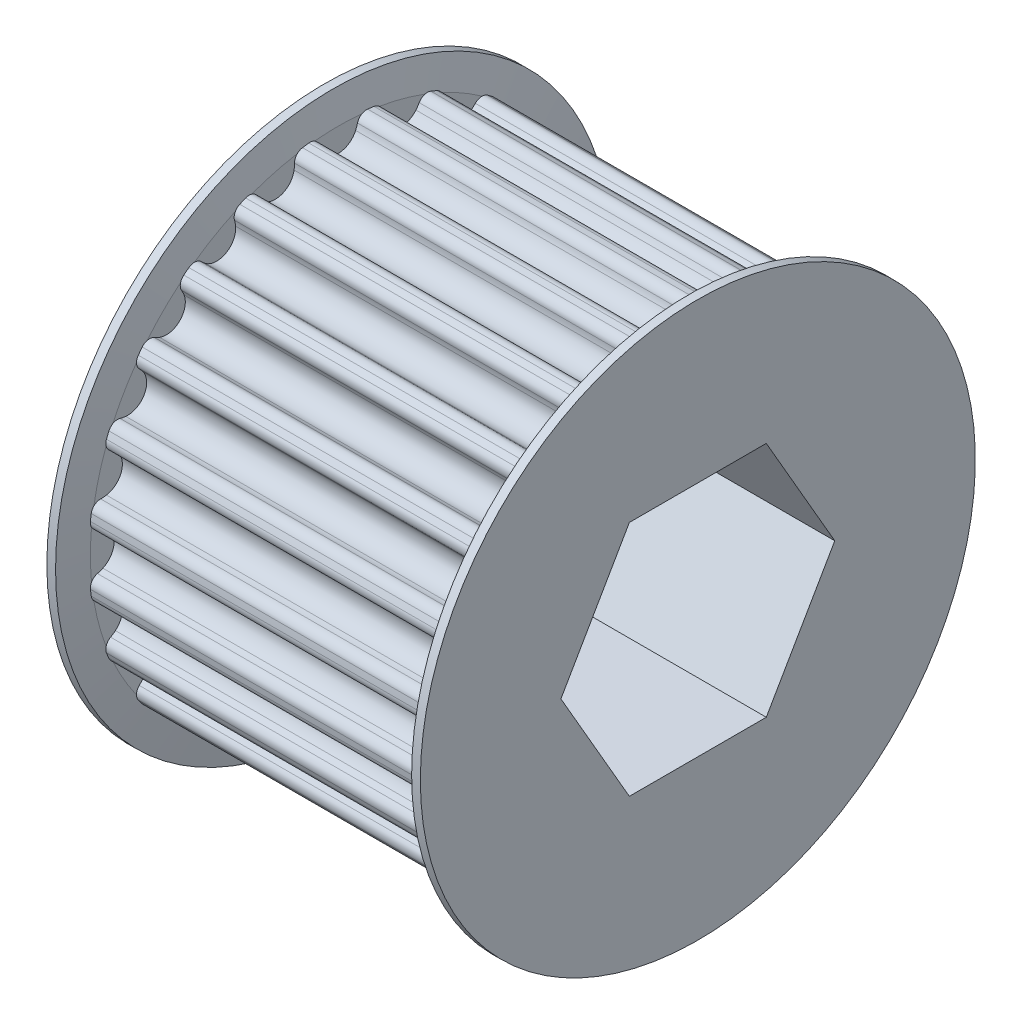
SolidWorks part; units mm, degrees
material "PET"
ref_plane "Front" through (0, 0, 0) normal (0, 0, 1) x (1, 0, 0)
ref_plane "Top" through (0, 0, 0) normal (0, 1, 0) x (1, 0, 0)
ref_plane "Right" through (0, 0, 0) normal (1, 0, 0) x (0, 0, -1)
sketch "Sketch1" plane through (0, 0, 0) normal (1, 0, 0) x (0, 0, -1)
  arc A0 (5.5576, 11.6856) -> (5.2736, 12.2806) centre (5.0763, 11.8212) ccw
  arc A1 (5.2736, 12.2806) -> (4.9547, 12.4127) centre (0, 0) ccw
  arc A2 (4.9547, 12.4127) -> (4.3332, 12.1928) centre (4.7694, 11.9483) ccw
  arc A3 (4.1589, 11.936) -> (4.3332, 12.1928) centre (2.7488, 13.0808) ccw
  arc A4 (2.3663, 12.4163) -> (4.1589, 11.936) centre (3.3699, 12.5766) ccw
  arc A5 (2.3437, 12.7258) -> (2.3663, 12.4163) centre (4.1598, 12.7027) ccw
  arc A6 (2.3437, 12.7258) -> (1.9154, 13.2271) centre (1.8438, 12.7322) ccw
  arc A7 (1.9154, 13.2271) -> (1.5733, 13.2721) centre (0, 0) ccw
  arc A8 (1.5733, 13.2721) -> (1.0298, 12.8988) centre (1.5144, 12.7756) ccw
  arc A9 (0.9279, 12.6057) -> (1.0298, 12.8988) centre (-0.7304, 13.3465) ccw
  arc A10 (-0.9279, 12.6057) -> (0.9279, 12.6057) centre (0, 13.0202) ccw
  arc A11 (-1.0298, 12.8988) -> (-0.9279, 12.6057) centre (0.7304, 13.3465) ccw
  arc A12 (-1.0298, 12.8988) -> (-1.5733, 13.2721) centre (-1.5144, 12.7756) ccw
  arc A13 (-1.5733, 13.2721) -> (-1.9154, 13.2271) centre (0, 0) ccw
  arc A14 (-1.9154, 13.2271) -> (-2.3437, 12.7258) centre (-1.8438, 12.7322) ccw
  arc A15 (-2.3663, 12.4163) -> (-2.3437, 12.7258) centre (-4.1598, 12.7027) ccw
  arc A16 (-4.1589, 11.936) -> (-2.3663, 12.4163) centre (-3.3699, 12.5766) ccw
  arc A17 (-4.3332, 12.1928) -> (-4.1589, 11.936) centre (-2.7488, 13.0808) ccw
  arc A18 (-4.3332, 12.1928) -> (-4.9547, 12.4127) centre (-4.7694, 11.9483) ccw
  arc A19 (-4.9547, 12.4127) -> (-5.2736, 12.2806) centre (0, 0) ccw
  arc A20 (-5.2736, 12.2806) -> (-5.5576, 11.6856) centre (-5.0763, 11.8212) ccw
  arc A21 (-5.4993, 11.3808) -> (-5.5576, 11.6856) centre (-7.3058, 11.1932) ccw
  arc A22 (-7.1064, 10.4529) -> (-5.4993, 11.3808) centre (-6.5101, 11.2758) ccw
  arc A23 (-7.3413, 10.6558) -> (-7.1064, 10.4529) centre (-6.0407, 11.9236) ccw
  arc A24 (-7.3413, 10.6558) -> (-7.9986, 10.7074) centre (-7.6993, 10.3068) ccw
  arc A25 (-7.9986, 10.7074) -> (-8.2723, 10.4973) centre (0, 0) ccw
  arc A26 (-8.2723, 10.4973) -> (-8.3927, 9.849) centre (-7.9628, 10.1045) ccw
  arc A27 (-8.2575, 9.5697) -> (-8.3927, 9.849) centre (-9.9539, 8.9209) ccw
  arc A28 (-9.5697, 8.2575) -> (-8.2575, 9.5697) centre (-9.2067, 9.2067) ccw
  arc A29 (-9.849, 8.3927) -> (-9.5697, 8.2575) centre (-8.9209, 9.9539) ccw
  arc A30 (-9.849, 8.3927) -> (-10.4973, 8.2723) centre (-10.1045, 7.9628) ccw
  arc A31 (-10.4973, 8.2723) -> (-10.7074, 7.9986) centre (0, 0) ccw
  arc A32 (-10.7074, 7.9986) -> (-10.6558, 7.3413) centre (-10.3068, 7.6993) ccw
  arc A33 (-10.4529, 7.1064) -> (-10.6558, 7.3413) centre (-11.9236, 6.0407) ccw
  arc A34 (-11.3808, 5.4993) -> (-10.4529, 7.1064) centre (-11.2758, 6.5101) ccw
  arc A35 (-11.6856, 5.5576) -> (-11.3808, 5.4993) centre (-11.1932, 7.3058) ccw
  arc A36 (-11.6856, 5.5576) -> (-12.2806, 5.2736) centre (-11.8212, 5.0763) ccw
  arc A37 (-12.2806, 5.2736) -> (-12.4127, 4.9547) centre (0, 0) ccw
  arc A38 (-12.4127, 4.9547) -> (-12.1928, 4.3332) centre (-11.9483, 4.7694) ccw
  arc A39 (-11.936, 4.1589) -> (-12.1928, 4.3332) centre (-13.0808, 2.7488) ccw
  arc A40 (-12.4163, 2.3663) -> (-11.936, 4.1589) centre (-12.5766, 3.3699) ccw
  arc A41 (-12.7258, 2.3437) -> (-12.4163, 2.3663) centre (-12.7027, 4.1598) ccw
  arc A42 (-12.7258, 2.3437) -> (-13.2271, 1.9154) centre (-12.7322, 1.8438) ccw
  arc A43 (-13.2271, 1.9154) -> (-13.2721, 1.5733) centre (0, 0) ccw
  arc A44 (-13.2721, 1.5733) -> (-12.8988, 1.0298) centre (-12.7756, 1.5144) ccw
  arc A45 (-12.6057, 0.9279) -> (-12.8988, 1.0298) centre (-13.3465, -0.7304) ccw
  arc A46 (-12.6057, -0.9279) -> (-12.6057, 0.9279) centre (-13.0202, 0) ccw
  arc A47 (-12.8988, -1.0298) -> (-12.6057, -0.9279) centre (-13.3465, 0.7304) ccw
  arc A48 (-12.8988, -1.0298) -> (-13.2721, -1.5733) centre (-12.7756, -1.5144) ccw
  arc A49 (-13.2721, -1.5733) -> (-13.2271, -1.9154) centre (0, 0) ccw
  arc A50 (-13.2271, -1.9154) -> (-12.7258, -2.3437) centre (-12.7322, -1.8438) ccw
  arc A51 (-12.4163, -2.3663) -> (-12.7258, -2.3437) centre (-12.7027, -4.1598) ccw
  arc A52 (-11.936, -4.1589) -> (-12.4163, -2.3663) centre (-12.5766, -3.3699) ccw
  arc A53 (-12.1928, -4.3332) -> (-11.936, -4.1589) centre (-13.0808, -2.7488) ccw
  arc A54 (-12.1928, -4.3332) -> (-12.4127, -4.9547) centre (-11.9483, -4.7694) ccw
  arc A55 (-12.4127, -4.9547) -> (-12.2806, -5.2736) centre (0, 0) ccw
  arc A56 (-12.2806, -5.2736) -> (-11.6856, -5.5576) centre (-11.8212, -5.0763) ccw
  arc A57 (-11.3808, -5.4993) -> (-11.6856, -5.5576) centre (-11.1932, -7.3058) ccw
  arc A58 (-10.4529, -7.1064) -> (-11.3808, -5.4993) centre (-11.2758, -6.5101) ccw
  arc A59 (-10.6558, -7.3413) -> (-10.4529, -7.1064) centre (-11.9236, -6.0407) ccw
  arc A60 (-10.6558, -7.3413) -> (-10.7074, -7.9986) centre (-10.3068, -7.6993) ccw
  arc A61 (-10.7074, -7.9986) -> (-10.4973, -8.2723) centre (0, 0) ccw
  arc A62 (-10.4973, -8.2723) -> (-9.849, -8.3927) centre (-10.1045, -7.9628) ccw
  arc A63 (-9.5697, -8.2575) -> (-9.849, -8.3927) centre (-8.9209, -9.9539) ccw
  arc A64 (-8.2575, -9.5697) -> (-9.5697, -8.2575) centre (-9.2067, -9.2067) ccw
  arc A65 (-8.3927, -9.849) -> (-8.2575, -9.5697) centre (-9.9539, -8.9209) ccw
  arc A66 (-8.3927, -9.849) -> (-8.2723, -10.4973) centre (-7.9628, -10.1045) ccw
  arc A67 (-8.2723, -10.4973) -> (-7.9986, -10.7074) centre (0, 0) ccw
  arc A68 (-7.9986, -10.7074) -> (-7.3413, -10.6558) centre (-7.6993, -10.3068) ccw
  arc A69 (-7.1064, -10.4529) -> (-7.3413, -10.6558) centre (-6.0407, -11.9236) ccw
  arc A70 (-5.4993, -11.3808) -> (-7.1064, -10.4529) centre (-6.5101, -11.2758) ccw
  arc A71 (-5.5576, -11.6856) -> (-5.4993, -11.3808) centre (-7.3058, -11.1932) ccw
  arc A72 (-5.5576, -11.6856) -> (-5.2736, -12.2806) centre (-5.0763, -11.8212) ccw
  arc A73 (-5.2736, -12.2806) -> (-4.9547, -12.4127) centre (0, 0) ccw
  arc A74 (-4.9547, -12.4127) -> (-4.3332, -12.1928) centre (-4.7694, -11.9483) ccw
  arc A75 (-4.1589, -11.936) -> (-4.3332, -12.1928) centre (-2.7488, -13.0808) ccw
  arc A76 (-2.3663, -12.4163) -> (-4.1589, -11.936) centre (-3.3699, -12.5766) ccw
  arc A77 (-2.3437, -12.7258) -> (-2.3663, -12.4163) centre (-4.1598, -12.7027) ccw
  arc A78 (-2.3437, -12.7258) -> (-1.9154, -13.2271) centre (-1.8438, -12.7322) ccw
  arc A79 (-1.9154, -13.2271) -> (-1.5733, -13.2721) centre (0, 0) ccw
  arc A80 (-1.5733, -13.2721) -> (-1.0298, -12.8988) centre (-1.5144, -12.7756) ccw
  arc A81 (-0.9279, -12.6057) -> (-1.0298, -12.8988) centre (0.7304, -13.3465) ccw
  arc A82 (0.9279, -12.6057) -> (-0.9279, -12.6057) centre (0, -13.0202) ccw
  arc A83 (1.0298, -12.8988) -> (0.9279, -12.6057) centre (-0.7304, -13.3465) ccw
  arc A84 (1.0298, -12.8988) -> (1.5733, -13.2721) centre (1.5144, -12.7756) ccw
  arc A85 (1.5733, -13.2721) -> (1.9154, -13.2271) centre (0, 0) ccw
  arc A86 (1.9154, -13.2271) -> (2.3437, -12.7258) centre (1.8438, -12.7322) ccw
  arc A87 (2.3663, -12.4163) -> (2.3437, -12.7258) centre (4.1598, -12.7027) ccw
  arc A88 (4.1589, -11.936) -> (2.3663, -12.4163) centre (3.3699, -12.5766) ccw
  arc A89 (4.3332, -12.1928) -> (4.1589, -11.936) centre (2.7488, -13.0808) ccw
  arc A90 (4.3332, -12.1928) -> (4.9547, -12.4127) centre (4.7694, -11.9483) ccw
  arc A91 (4.9547, -12.4127) -> (5.2736, -12.2806) centre (0, 0) ccw
  arc A92 (5.2736, -12.2806) -> (5.5576, -11.6856) centre (5.0763, -11.8212) ccw
  arc A93 (5.4993, -11.3808) -> (5.5576, -11.6856) centre (7.3058, -11.1932) ccw
  arc A94 (7.1064, -10.4529) -> (5.4993, -11.3808) centre (6.5101, -11.2758) ccw
  arc A95 (7.3413, -10.6558) -> (7.1064, -10.4529) centre (6.0407, -11.9236) ccw
  arc A96 (7.3413, -10.6558) -> (7.9986, -10.7074) centre (7.6993, -10.3068) ccw
  arc A97 (7.9986, -10.7074) -> (8.2723, -10.4973) centre (0, 0) ccw
  arc A98 (8.2723, -10.4973) -> (8.3927, -9.849) centre (7.9628, -10.1045) ccw
  arc A99 (8.2575, -9.5697) -> (8.3927, -9.849) centre (9.9539, -8.9209) ccw
  arc A100 (9.5697, -8.2575) -> (8.2575, -9.5697) centre (9.2067, -9.2067) ccw
  arc A101 (9.849, -8.3927) -> (9.5697, -8.2575) centre (8.9209, -9.9539) ccw
  arc A102 (9.849, -8.3927) -> (10.4973, -8.2723) centre (10.1045, -7.9628) ccw
  arc A103 (10.4973, -8.2723) -> (10.7074, -7.9986) centre (0, 0) ccw
  arc A104 (10.7074, -7.9986) -> (10.6558, -7.3413) centre (10.3068, -7.6993) ccw
  arc A105 (10.4529, -7.1064) -> (10.6558, -7.3413) centre (11.9236, -6.0407) ccw
  arc A106 (11.3808, -5.4993) -> (10.4529, -7.1064) centre (11.2758, -6.5101) ccw
  arc A107 (11.6856, -5.5576) -> (11.3808, -5.4993) centre (11.1932, -7.3058) ccw
  arc A108 (11.6856, -5.5576) -> (12.2806, -5.2736) centre (11.8212, -5.0763) ccw
  arc A109 (12.2806, -5.2736) -> (12.4127, -4.9547) centre (0, 0) ccw
  arc A110 (12.4127, -4.9547) -> (12.1928, -4.3332) centre (11.9483, -4.7694) ccw
  arc A111 (11.936, -4.1589) -> (12.1928, -4.3332) centre (13.0808, -2.7488) ccw
  arc A112 (12.4163, -2.3663) -> (11.936, -4.1589) centre (12.5766, -3.3699) ccw
  arc A113 (12.7258, -2.3437) -> (12.4163, -2.3663) centre (12.7027, -4.1598) ccw
  arc A114 (12.7258, -2.3437) -> (13.2271, -1.9154) centre (12.7322, -1.8438) ccw
  arc A115 (13.2271, -1.9154) -> (13.2721, -1.5733) centre (0, 0) ccw
  arc A116 (13.2721, -1.5733) -> (12.8988, -1.0298) centre (12.7756, -1.5144) ccw
  arc A117 (12.6057, -0.9279) -> (12.8988, -1.0298) centre (13.3465, 0.7304) ccw
  arc A118 (12.6057, 0.9279) -> (12.6057, -0.9279) centre (13.0202, 0) ccw
  arc A119 (12.8988, 1.0298) -> (12.6057, 0.9279) centre (13.3465, -0.7304) ccw
  arc A120 (12.8988, 1.0298) -> (13.2721, 1.5733) centre (12.7756, 1.5144) ccw
  arc A121 (13.2721, 1.5733) -> (13.2271, 1.9154) centre (0, 0) ccw
  arc A122 (13.2271, 1.9154) -> (12.7258, 2.3437) centre (12.7322, 1.8438) ccw
  arc A123 (12.4163, 2.3663) -> (12.7258, 2.3437) centre (12.7027, 4.1598) ccw
  arc A124 (11.936, 4.1589) -> (12.4163, 2.3663) centre (12.5766, 3.3699) ccw
  arc A125 (12.1928, 4.3332) -> (11.936, 4.1589) centre (13.0808, 2.7488) ccw
  arc A126 (12.1928, 4.3332) -> (12.4127, 4.9547) centre (11.9483, 4.7694) ccw
  arc A127 (12.4127, 4.9547) -> (12.2806, 5.2736) centre (0, 0) ccw
  arc A128 (12.2806, 5.2736) -> (11.6856, 5.5576) centre (11.8212, 5.0763) ccw
  arc A129 (11.3808, 5.4993) -> (11.6856, 5.5576) centre (11.1932, 7.3058) ccw
  arc A130 (10.4529, 7.1064) -> (11.3808, 5.4993) centre (11.2758, 6.5101) ccw
  arc A131 (10.6558, 7.3413) -> (10.4529, 7.1064) centre (11.9236, 6.0407) ccw
  arc A132 (10.6558, 7.3413) -> (10.7074, 7.9986) centre (10.3068, 7.6993) ccw
  arc A133 (10.7074, 7.9986) -> (10.4973, 8.2723) centre (0, 0) ccw
  arc A134 (10.4973, 8.2723) -> (9.849, 8.3927) centre (10.1045, 7.9628) ccw
  arc A135 (9.5697, 8.2575) -> (9.849, 8.3927) centre (8.9209, 9.9539) ccw
  arc A136 (8.2575, 9.5697) -> (9.5697, 8.2575) centre (9.2067, 9.2067) ccw
  arc A137 (8.3927, 9.849) -> (8.2575, 9.5697) centre (9.9539, 8.9209) ccw
  arc A138 (8.3927, 9.849) -> (8.2723, 10.4973) centre (7.9628, 10.1045) ccw
  arc A139 (8.2723, 10.4973) -> (7.9986, 10.7074) centre (0, 0) ccw
  arc A140 (7.9986, 10.7074) -> (7.3413, 10.6558) centre (7.6993, 10.3068) ccw
  arc A141 (7.1064, 10.4529) -> (7.3413, 10.6558) centre (6.0407, 11.9236) ccw
  arc A142 (5.4993, 11.3808) -> (7.1064, 10.4529) centre (6.5101, 11.2758) ccw
  arc A143 (5.5576, 11.6856) -> (5.4993, 11.3808) centre (7.3058, 11.1932) ccw
extrude "Boss-Extrude1" add sketch "Sketch1" along normal mid plane 18.508
sketch "Sketch2" plane through (0, 0, 0) normal (0, 0, 1) x (1, 0, 0)
  line L0 (-8.3357, 0) -> (8.3357, 0) construction
  line L1 (9.254, 13.2721) -> (-9.254, 13.2721) construction
  line L2 (-10, 4.7625) -> (-9.254, 4.7625)
  line L3 (-9.254, 4.7625) -> (-9.254, 13.2721)
  line L4 (-9.254, 13.2721) -> (-9.5339, 14.8596)
  line L5 (-9.5339, 14.8596) -> (-10, 14.8596)
  line L6 (-10, 14.8596) -> (-10, 4.7625)
  line L7 (-9.254, 11.6856) -> (-9.254, 11.3808) construction
  line L8 (0, 0) -> (0, 16.7777) construction
  line L9 (10, 14.8596) -> (10, 4.7625)
  line L10 (9.5339, 14.8596) -> (10, 14.8596)
  line L11 (9.254, 13.2721) -> (9.5339, 14.8596)
  line L12 (9.254, 4.7625) -> (9.254, 13.2721)
  line L13 (10, 4.7625) -> (9.254, 4.7625)
  point P4 (0, 0)
  dimension "D1" = 4.7625
  dimension "D2" = 0.746
  dimension "D4" = 1.5875
  dimension "D5" = 100
revolve "Revolve1" add sketch "Sketch2" angle 360 about L0
sketch "Sketch3" plane through (0, 0, 0) normal (1, 0, 0) x (0, 0, -1)
  line L1 (7.3323, 0) -> (3.6662, 6.35)
  line L2 (3.6662, 6.35) -> (-3.6662, 6.35)
  line L3 (-3.6662, 6.35) -> (-7.3323, 0)
  line L4 (-7.3323, 0) -> (-3.6662, -6.35)
  line L5 (-3.6662, -6.35) -> (3.6662, -6.35)
  line L6 (3.6662, -6.35) -> (7.3323, 0)
  circle A0 centre (0, 0) radius 6.35 construction
  dimension "D1" = 12.7
extrude "Cut-Extrude1" cut sketch "Sketch3" against normal through all both and the other way through all
